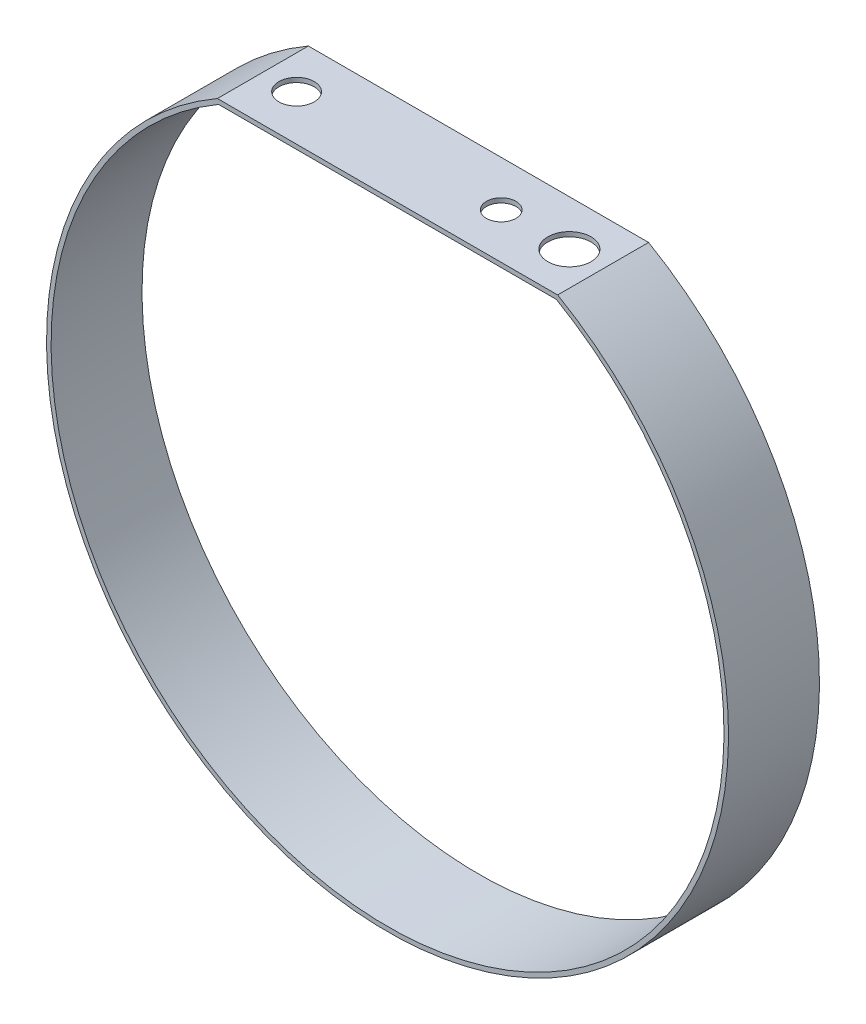
SolidWorks part; units mm, degrees
ref_plane "Face" through (0, 0, 0) normal (0, 0, 1) x (1, 0, 0)
ref_plane "Dessus" through (0, 0, 0) normal (0, 1, 0) x (1, 0, 0)
ref_plane "Droite" through (0, 0, 0) normal (1, 0, 0) x (0, 0, -1)
sketch "Esquisse1" plane through (0, 0, 0) normal (0, 0, 1) x (1, 0, 0)
  line L0 (-74.8331, 130) -> (74.8331, 130)
  line L1 (-74.2967, 128) -> (74.2967, 128)
  arc A0 (-74.8331, 130) -> (74.8331, 130) centre (0, 0) ccw
  arc A1 (-74.2967, 128) -> (74.2967, 128) centre (0, 0) ccw
  dimension "D1" = 300
  dimension "D2" = 2
  dimension "D3" = 130
  dimension "D4" = 2
extrude "Boss.-Extru.1" add sketch "Esquisse1" along normal blind 40
sketch "Esquisse2" plane through (0, 130, 0) normal (0, 1, 0) x (1, 0, 0)
  line L0 (74.8331, 0) -> (-74.8331, 0) construction
  circle A0 centre (60, -20) radius 9.5
  circle A1 centre (-60, -20) radius 7.75
  circle A2 centre (30, -20) radius 6.5
  dimension "D1" = 19
  dimension "D2" = 60
  dimension "D3" = 13
  dimension "D4" = 30
  dimension "D7" = 15.5
  dimension "D8" = 20
  dimension "D9" = 60
extrude "Enlèv. mat.-Extru.1" cut sketch "Esquisse2" against normal up to next
